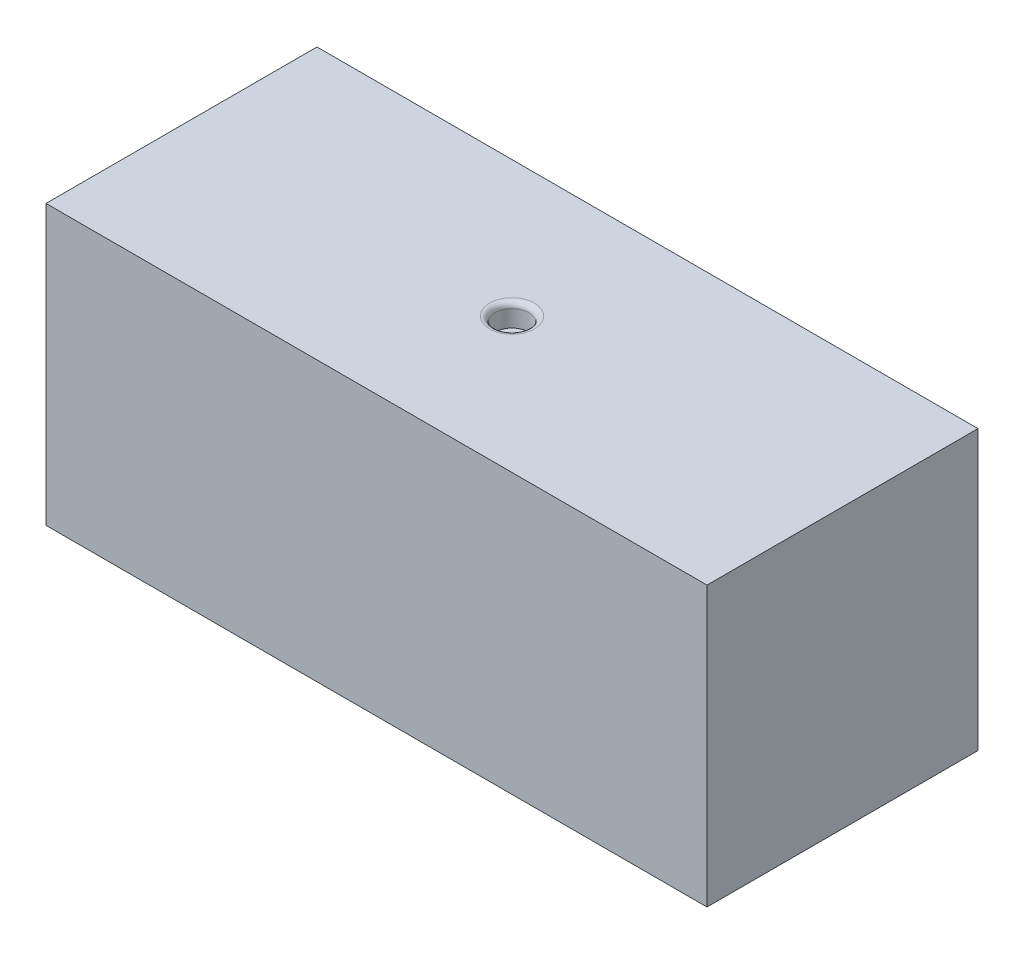
SolidWorks part; units mm, degrees
ref_plane "Front Plane" through (0, 0, 0) normal (0, 0, 1) x (1, 0, 0)
ref_plane "Top Plane" through (0, 0, 0) normal (0, 1, 0) x (1, 0, 0)
ref_plane "Right Plane" through (0, 0, 0) normal (1, 0, 0) x (0, 0, -1)
sketch "Sketch1" plane through (0, 0, 0) normal (0, 0, 1) x (1, 0, 0)
  line L1 (-88.9, -127) -> (88.9, -127)
  line L2 (-88.9, -127) -> (-88.9, 127)
  line L3 (-88.9, 127) -> (88.9, 127)
  line L4 (88.9, -127) -> (88.9, 127)
  line L5 (-88.9, -127) -> (88.9, 127) construction
  line L6 (-88.9, 127) -> (88.9, -127) construction
  point P0 (0, 0)
  dimension "D1" = 177.8
  dimension "D2" = 254
extrude "Boss-Extrude1" add sketch "Sketch1" along normal mid plane 72.89
shell "Shell1" thickness 3
sketch "Sketch2" plane through (0, 0, 33.445) normal (0, 0, -1) x (-1, 0, 0)
  line L0 (85.9, -124) -> (-85.9, -124) construction
  circle A0 centre (0, -4) radius 22
  dimension "D1" = 44
  dimension "D2" = 120
extrude "Cut-Extrude1" cut sketch "Sketch2" against normal blind 3
sketch "Sketch3" plane through (0, 0, -33.445) normal (0, 0, 1) x (1, 0, 0)
  line L0 (85.9, 124) -> (-85.9, 124) construction
  line L1 (-85.9, 124) -> (-85.9, -124) construction
  circle A0 centre (-20.9, 34) radius 5
  dimension "D3" = 10
  dimension "D1" = 90
  dimension "D2" = 65
extrude "Cut-Extrude2" cut sketch "Sketch3" against normal blind 3
sketch "Sketch12" plane through (0, 124, 0) normal (0, -1, 0) x (1, 0, 0)
  line L0 (85.9, -33.445) -> (-85.9, -33.445) construction
  line L1 (6, 33.445) -> (-6, 33.445)
  line L2 (6, 33.445) -> (6, -33.445)
  line L3 (6, -33.445) -> (-6, -33.445)
  line L4 (-6, 33.445) -> (-6, -33.445)
  line L5 (6, 33.445) -> (-6, -33.445) construction
  line L6 (6, -33.445) -> (-6, 33.445) construction
  point P0 (0, 0)
  dimension "D1" = 12
extrude "Boss-Extrude5" add sketch "Sketch12" along normal blind 6
sketch "Sketch10" plane through (0, 127, 0) normal (0, 1, 0) x (1, 0, 0)
  circle A0 centre (0, 0) radius 4.525
  dimension "D1" = 9.05
extrude "Cut-Extrude8" cut sketch "Sketch10" against normal blind 6 contours A0
ref_plane "Plane2" through (0, 52, 0) normal (0, 1, 0) x (1, 0, 0)
split "Split2" trim tools "Plane2" bodies to split 123 resulting bodies 126 127
sketch "Sketch13" plane through (0, 52, 0) normal (0, 1, 0) x (1, 0, 0)
  line L4 (-85.9, 33.445) -> (-85.9, -33.445)
  line L5 (-85.9, -33.445) -> (85.9, -33.445)
  line L6 (85.9, -33.445) -> (85.9, 33.445)
  line L7 (85.9, 33.445) -> (-85.9, 33.445)
  line L8 (-87.4, 34.945) -> (-87.4, -34.945)
  line L9 (-87.4, -34.945) -> (87.4, -34.945)
  line L10 (87.4, -34.945) -> (87.4, 34.945)
  line L11 (87.4, 34.945) -> (-87.4, 34.945)
  line L12 (-87.4, 34.945) -> (-87.4, -34.945)
  line L13 (-87.4, -34.945) -> (87.4, -34.945)
  line L14 (87.4, -34.945) -> (87.4, 34.945)
  line L15 (87.4, 34.945) -> (-87.4, 34.945)
  dimension "D1" = 1.5
  dimension "D2" = 1.5
extrude "Boss-Extrude6" add sketch "Sketch13" along normal blind 10
sketch "Sketch14" plane through (0, 52, 0) normal (0, -1, 0) x (1, 0, 0)
  line L7 (-85.9, 33.445) -> (-85.9, -33.445)
  line L8 (-85.9, -33.445) -> (85.9, -33.445)
  line L9 (85.9, -33.445) -> (85.9, 33.445)
  line L10 (85.9, 33.445) -> (-85.9, 33.445)
  line L11 (-87.65, 35.195) -> (-87.65, -35.195)
  line L12 (-87.65, -35.195) -> (87.65, -35.195)
  line L13 (87.65, -35.195) -> (87.65, 35.195)
  line L14 (87.65, 35.195) -> (-87.65, 35.195)
  line L15 (-87.65, 35.195) -> (-87.65, -35.195)
  line L16 (-87.65, -35.195) -> (87.65, -35.195)
  line L17 (87.65, -35.195) -> (87.65, 35.195)
  line L18 (87.65, 35.195) -> (-87.65, 35.195)
  dimension "D1" = 1.75
  dimension "D2" = 1.75
extrude "Cut-Extrude9" cut sketch "Sketch14" against normal blind 25
sketch "Sketch17" plane through (0, -124, 0) normal (0, 1, 0) x (1, 0, 0)
  line L1 (-85.9, 33.445) -> (85.9, 33.445)
  line L2 (-85.9, 33.445) -> (-85.9, -33.445)
  line L3 (-85.9, -33.445) -> (85.9, -33.445)
  line L4 (85.9, 33.445) -> (85.9, -33.445)
  line L5 (-85.9, 33.445) -> (85.9, -33.445) construction
  line L6 (-85.9, -33.445) -> (85.9, 33.445) construction
  point P4 (0, 0)
extrude "Boss-Extrude7" add sketch "Sketch17" along normal blind 2
sketch "Sketch15" plane through (0, -127, 0) normal (0, -1, 0) x (1, 0, 0)
  circle A0 centre (0, 0) radius 8.05
  dimension "D1" = 16.1
extrude "Cut-Extrude10" cut sketch "Sketch15" against normal blind 5
sketch "Sketch18" plane through (0, -127, 0) normal (0, -1, 0) x (1, 0, 0)
  line L0 (-1000, 0) -> (49000, 0) construction
  line L1 (0, 0) -> (-7.7782, 7.7782) construction
  line L2 (0, 0) -> (-7.7782, 7.7782) construction
  circle A0 centre (0, 0) radius 11 construction
  circle A1 centre (-7.7782, 7.7782) radius 2.875
  circle A2 centre (0, 0) radius 11 construction
  circle A3 centre (7.7782, 7.7782) radius 2.875
  circle A4 centre (0, 0) radius 11 construction
  circle A5 centre (7.7782, -7.7782) radius 2.875
  circle A6 centre (0, 0) radius 11 construction
  circle A7 centre (-7.7782, -7.7782) radius 2.875
  dimension "D1" = 22
  dimension "D3" = 5.75
  dimension "D2" = 45
  dimension "D4" = 4
extrude "Cut-Extrude11" cut sketch "Sketch18" against normal blind 4.7
delete or keep bodies "Body-Delete/Keep 1" type delete bodies bodies 132
fillet "Fillet1" radius 1.5 1 edges at (0, 127, 4.525)
